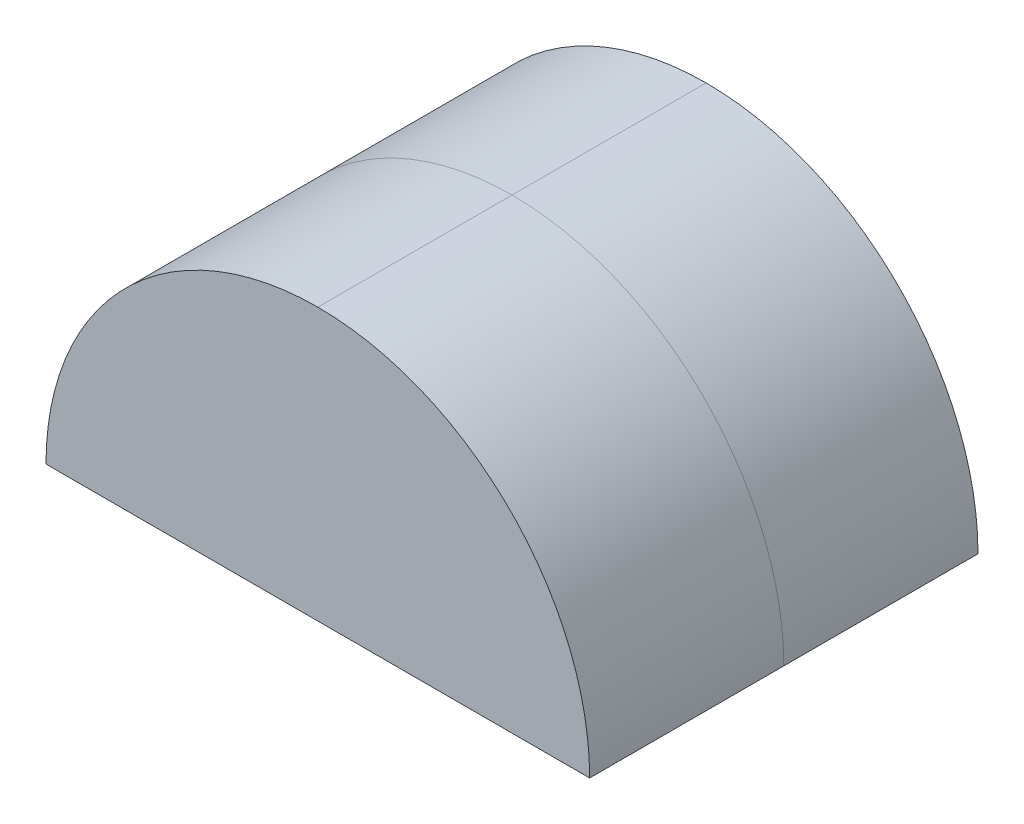
SolidWorks part; units mm, degrees
ref_plane "Plane1" through (0, 0, 0) normal (0, 0, 1) x (1, 0, 0)
ref_plane "Plane2" through (0, 0, 0) normal (0, 1, 0) x (1, 0, 0)
ref_plane "Plane3" through (0, 0, 0) normal (1, 0, 0) x (0, 0, -1)
other "Configuration Table"
sketch "Sketch1" plane through (0, 0, 0) normal (0, 0, 1) x (1, 0, 0)
  line L0 (-134.4722, 0) -> (154.4802, 0) construction
  line L1 (0, 91.1991) -> (0, -101.9011) construction
  line L2 (17.78, 0) -> (-17.78, 0)
  arc A0 (-17.78, 0) -> (17.78, 0) centre (0, 0) cw
  point P7 (0, 0)
  dimension "D1" = 17.78
extrude "Base-Extrude" add sketch "Sketch1" along normal blind 25.4
sketch "Sketch4" plane through (0, 0, 0) normal (0, -1, 0) x (1, 0, 0)
  line L0 (0, -5.7094) -> (0, 30.54)
split line "Split Line4"
sketch "Sketch6" plane through (0, 0, 0) normal (0, -1, 0) x (1, 0, 0)
  line L0 (0, 12.7) -> (-17.78, 12.7) construction
  line L1 (17.78, 12.7) -> (0, 12.7) construction
  line L2 (0, 12.7) -> (-17.78, 12.7)
  line L3 (17.78, 12.7) -> (0, 12.7)
split line "Split Line6"
